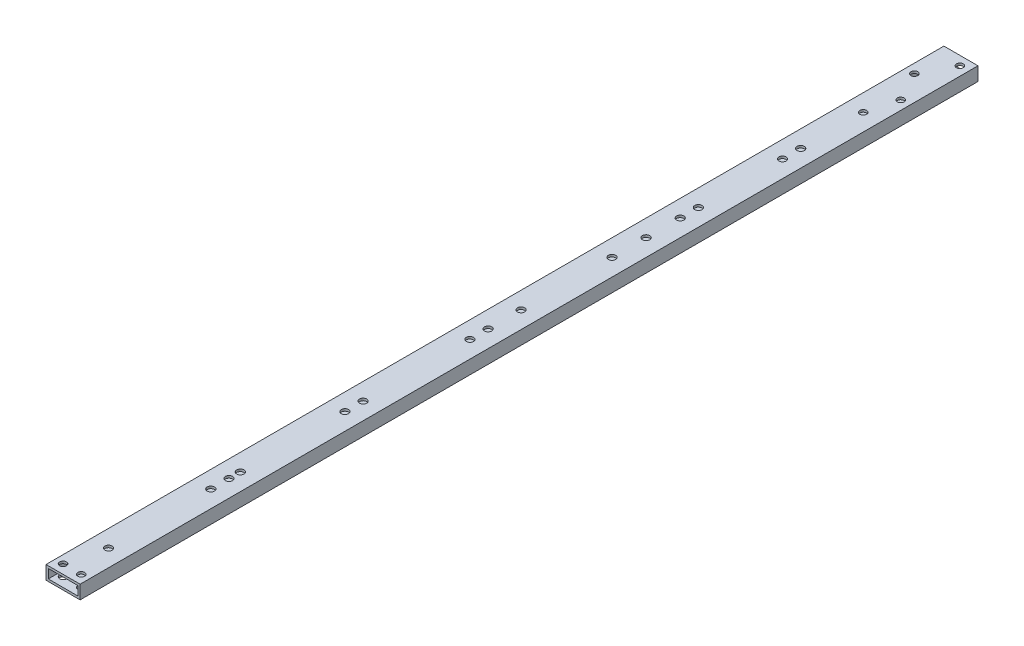
SolidWorks part; units mm, degrees
material "6061 合金"
ref_plane "前视基准面" through (0, 0, 0) normal (0, 0, 1) x (1, 0, 0)
ref_plane "上视基准面" through (0, 0, 0) normal (0, 1, 0) x (1, 0, 0)
ref_plane "右视基准面" through (0, 0, 0) normal (1, 0, 0) x (0, 0, -1)
sketch "草图1" plane through (0, 0, 0) normal (0, 0, 1) x (1, 0, 0)
  line L1 (7.5, -3) -> (-7.5, -3)
  line L2 (7.5, -3) -> (7.5, 3)
  line L3 (7.5, 3) -> (-7.5, 3)
  line L4 (-7.5, -3) -> (-7.5, 3)
  line L5 (7.5, -3) -> (-7.5, 3) construction
  line L6 (7.5, 3) -> (-7.5, -3) construction
  line L7 (6.5, -2) -> (-6.5, -2)
  line L8 (6.5, -2) -> (6.5, 2)
  line L9 (6.5, 2) -> (-6.5, 2)
  line L10 (-6.5, -2) -> (-6.5, 2)
  line L11 (6.5, -2) -> (-6.5, 2) construction
  line L12 (6.5, 2) -> (-6.5, -2) construction
  point P0 (0, 0)
  point P6 (0, 0)
  dimension "D1" = 6
  dimension "D2" = 15
  dimension "D3" = 1
  dimension "D4" = 1
extrude "凸台-拉伸1" add sketch "草图1" along normal blind 400
sketch "草图2" plane through (0, -3, 0) normal (0, -1, 0) x (1, 0, 0)
  line L0 (3.5, 0) -> (3.5, 35) construction
  line L1 (-7.5, 0) -> (7.5, 0) construction
  line L2 (7.5, 400) -> (7.5, 0) construction
  line L3 (-3.5, 22) -> (12.9435, 22) construction
  circle A0 centre (3.5, 35) radius 1.5
  circle A1 centre (3.5, 9) radius 1.5
  circle A2 centre (-3.5, 22) radius 1.5
  circle A3 centre (0, 48) radius 1.5
  dimension "D2" = 3
  dimension "D1" = 26
  dimension "D3" = 22
  dimension "D4" = 4
  dimension "D5" = 7
  dimension "D6" = 13
extrude "切除-拉伸1" cut sketch "草图2" against normal blind 10
sketch "草图3" plane through (0, 3, 0) normal (0, 1, 0) x (1, 0, 0)
  line L0 (7.5, 0) -> (-7.5, 0) construction
  line L1 (7.5, -400) -> (-7.5, -400) construction
  line L2 (0, -400) -> (0, -380) construction
  circle A0 centre (0, -335) radius 1.6
  circle A1 centre (0, -327) radius 1.6
  circle A2 centre (0, -198.5) radius 1.6
  circle A3 centre (0, -276) radius 1.6
  circle A4 centre (0, -268) radius 1.6
  circle A5 centre (4, -396) radius 1.5
  circle A6 centre (-4, -396) radius 1.5
  circle A8 centre (0, -221) radius 1.6
  circle A9 centre (0, -213) radius 1.6
  circle A10 centre (0, -158.5) radius 1.6
  circle A11 centre (0, -143.5) radius 1.6
  circle A12 centre (0, -120.5) radius 1.6
  circle A13 centre (0, -128.5) radius 1.6
  circle A18 centre (0, -75.5) radius 1.6
  circle A19 centre (0, -83.5) radius 1.6
  circle A20 centre (0, -380) radius 1.6
  circle A21 centre (0, -322) radius 1.6
  dimension "D1" = 3.2
  dimension "D12" = 5
  dimension "D17" = 3
  dimension "D2" = 8
  dimension "D3" = 75.5
  dimension "D4" = 8
  dimension "D5" = 15
  dimension "D6" = 8
  dimension "D7" = 15
  dimension "D8" = 8
  dimension "D9" = 54.5
  dimension "D10" = 58
  dimension "D11" = 20
  dimension "D13" = 37
  dimension "D14" = 40
  dimension "D15" = 8
  dimension "D16" = 55
  dimension "D18" = 8
  dimension "D19" = 4
extrude "切除-拉伸2" cut sketch "草图3" against normal through all
sketch "草图4" plane through (0, 3, 0) normal (0, 1, 0) x (1, 0, 0)
  line L1 (-11.6245, 4.9365) -> (11.6245, 4.9365)
  line L2 (-11.6245, 4.9365) -> (-11.6245, -5)
  line L3 (-11.6245, -5) -> (11.6245, -5)
  line L4 (11.6245, 4.9365) -> (11.6245, -5)
  line L5 (-11.6245, 4.9365) -> (11.6245, -5) construction
  line L6 (-11.6245, -5) -> (11.6245, 4.9365) construction
  line L7 (7.5, 0) -> (-7.5, 0) construction
  dimension "D1" = 5
extrude "切除-拉伸3" cut sketch "草图4" against normal blind 10
